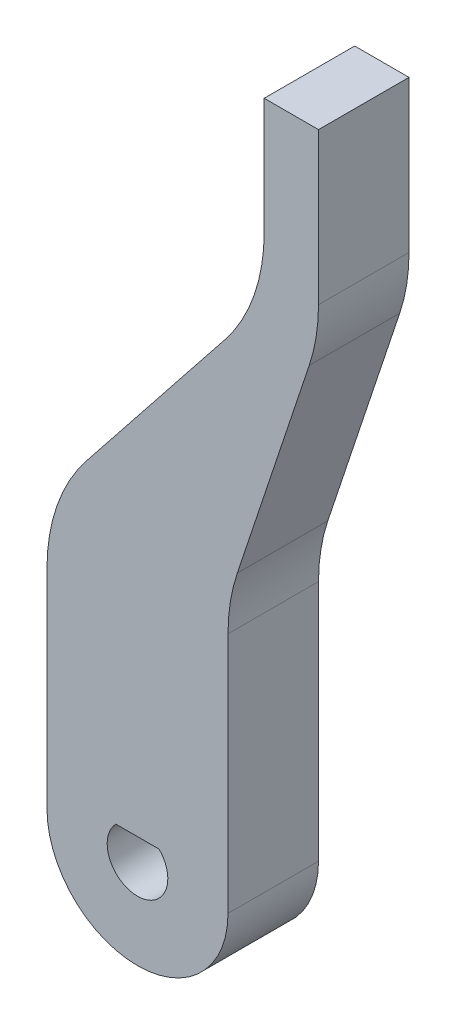
SolidWorks part; units mm, degrees
ref_plane "Front Plane" through (0, 0, 0) normal (0, 0, 1) x (1, 0, 0)
ref_plane "Top Plane" through (0, 0, 0) normal (0, 1, 0) x (1, 0, 0)
ref_plane "Right Plane" through (0, 0, 0) normal (1, 0, 0) x (0, 0, -1)
sketch "Sketch1" plane through (0, 0, 0) normal (0, 0, 1) x (1, 0, 0)
  line L1 (-5, 0) -> (-5, 15)
  line L2 (7, 40) -> (7, 30.0963)
  line L3 (7, 40) -> (10, 40)
  line L4 (10, 40) -> (10, 30)
  line L5 (10, 30) -> (5, 15)
  line L6 (5, 15) -> (5, 0)
  line L7 (7, 30.0963) -> (-5, 15)
  line L8 (-1.1937, 1.175) -> (1.1937, 1.175)
  arc A0 (-5, 0) -> (5, 0) centre (0, 0) ccw
  arc A2 (-1.1937, 1.175) -> (1.1937, 1.175) centre (0, 0) ccw
  dimension "D1" = 10
  dimension "D2" = 3.35
  dimension "D3" = 1.175
  dimension "D4" = 10
  dimension "D5" = 40
  dimension "D6" = 15
  dimension "D7" = 3
  dimension "D8" = 10
extrude "Boss-Extrude1" add sketch "Sketch1" along normal blind 5
fillet "Fillet1" radius 10 2 edges at (10, 30, 2.5) (-5, 15, 2.5)
fillet "Fillet2" radius 10 2 edges at (5, 15, 2.5) (7, 30.0963, 2.5)
